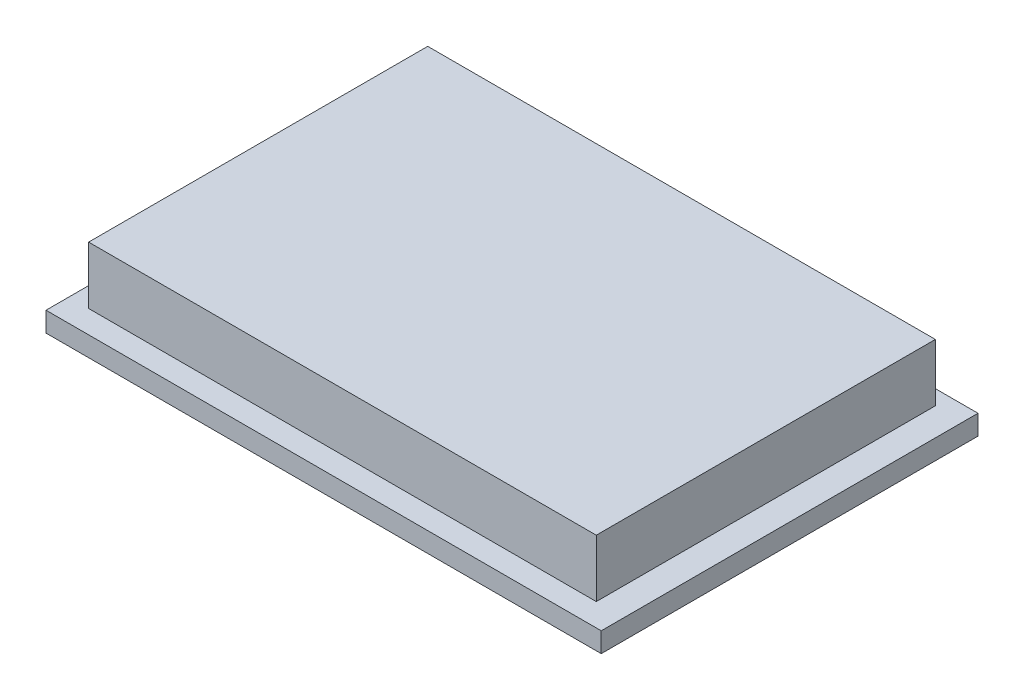
SolidWorks part; units mm, degrees
ref_plane "Front Plane" through (0, 0, 0) normal (0, 0, 1) x (1, 0, 0)
ref_plane "Top Plane" through (0, 0, 0) normal (0, 1, 0) x (1, 0, 0)
ref_plane "Right Plane" through (0, 0, 0) normal (1, 0, 0) x (0, 0, -1)
sketch "Sketch1" plane through (0, 0, 0) normal (0, 1, 0) x (1, 0, 0)
  line L1 (-64, -42.75) -> (64, -42.75)
  line L2 (-64, -42.75) -> (-64, 42.75)
  line L3 (-64, 42.75) -> (64, 42.75)
  line L4 (64, -42.75) -> (64, 42.75)
  line L5 (-64, -42.75) -> (64, 42.75) construction
  line L6 (-64, 42.75) -> (64, -42.75) construction
  point P0 (0, 0)
  dimension "D1" = 85.5
  dimension "D2" = 128
extrude "Boss-Extrude1" add sketch "Sketch1" along normal blind 14.5
ref_plane "Plane1" through (0, -1, 0) normal (0, -1, 0) x (1, 0, 0)
sketch "Sketch3" plane through (0, -1, 0) normal (0, -1, 0) x (1, 0, 0)
  line L1 (70, -47.5) -> (-70, -47.5)
  line L2 (70, -47.5) -> (70, 47.5)
  line L3 (70, 47.5) -> (-70, 47.5)
  line L4 (-70, -47.5) -> (-70, 47.5)
  line L5 (70, -47.5) -> (-70, 47.5) construction
  line L6 (70, 47.5) -> (-70, -47.5) construction
  point P0 (0, 0)
  dimension "D1" = 140
  dimension "D2" = 95
extrude "Boss-Extrude3" add sketch "Sketch3" along normal blind 5 separate body
ref_plane "Plane2" through (1, 0, 0) normal (1, 0, 0) x (0, 0, -1)
sketch "Sketch5" plane through (1, 0, 0) normal (1, 0, 0) x (0, 0, -1)
  line L0 (47.5, -6) -> (-47.5, -6) construction
  line L1 (-40, -6) -> (-40, -12.35) construction
  line L2 (0, -6) -> (0, -16.5846) construction
  circle A0 centre (0, -6) radius 40 construction
  circle A1 centre (-40, -12.35) radius 3.9687
  circle A2 centre (-40, -6) radius 6.35 construction
  circle A3 centre (40, -12.35) radius 3.9688
  dimension "D1" = 80
